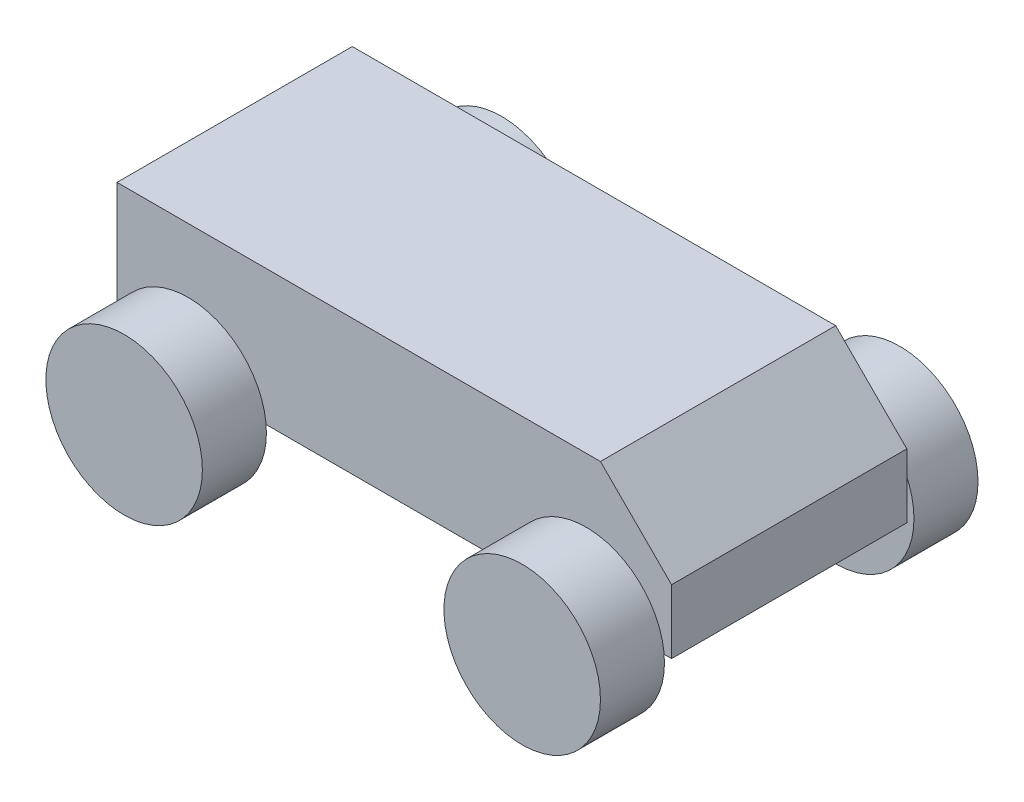
SolidWorks part; units mm, degrees
ref_plane "Front Plane" through (0, 0, 0) normal (0, 0, 1) x (1, 0, 0)
ref_plane "Top Plane" through (0, 0, 0) normal (0, 1, 0) x (1, 0, 0)
ref_plane "Right Plane" through (0, 0, 0) normal (1, 0, 0) x (0, 0, -1)
sketch "Sketch1" plane through (0, 0, 0) normal (0, 1, 0) x (1, 0, 0)
  line L1 (-495, 210) -> (495, 210)
  line L2 (-495, 210) -> (-495, -210)
  line L3 (-495, -210) -> (495, -210)
  line L4 (495, 210) -> (495, -210)
  line L5 (-495, 210) -> (495, -210) construction
  line L6 (-495, -210) -> (495, 210) construction
  point P0 (0, 0)
  dimension "D1" = 420
  dimension "D2" = 990
extrude "Boss-Extrude1" add sketch "Sketch1" along normal blind 241.3
sketch "Sketch2" plane through (0, 0, 210) normal (0, 0, 1) x (1, 0, 0)
  line L0 (-495, 0) -> (495, 0) construction
  line L1 (-355.3, 0) -> (0, 0) construction
  line L2 (0, 0) -> (355.3, 0) construction
  line L3 (-495, 241.3) -> (-495, 0) construction
  circle A0 centre (-355.3, 0) radius 139.7
  circle A1 centre (355.3, 0) radius 139.7
  dimension "D1" = 279.4
extrude "Boss-Extrude2" add sketch "Sketch2" along normal blind 114.3 from offset 12.7 separate body
mirror "Mirror2" about plane through (0, 0, 0) normal (0, 0, 1) of bodies 103 102
sketch "Sketch3" plane through (0, 0, 337) normal (0, 0, 1) x (1, 0, 0)
  circle A0 centre (-355.3, 0) radius 25.4
  circle A1 centre (355.3, 0) radius 25.4
  dimension "D1" = 50.8
extrude "Boss-Extrude3" add sketch "Sketch3" against normal up to surface (674 mm away) up to face at (495, 0, -337)
chamfer "Chamfer1" distance 127 angle 45 1 edges at (495, 241.3, 0)
sketch "Sketch4" plane through (0, 0, 210) normal (0, 0, 1) x (1, 0, 0)
  line L1 (-495, 241.3) -> (368, 241.3) construction
  line L2 (355.3, -139.7) -> (-355.3, -139.7) construction
  line L3 (-495, 241.3) -> (-495, 0) construction
  arc A0 (-660.1, 241.3) -> (-876, -139.7) centre (-1078.9553, 226.9797) cw
  circle A3 centre (-355.3, 0) radius 139.7 construction
  dimension "D1" = 381
  dimension "D3" = 419.1
  dimension "D2" = 165.1
extrude "Extrude-Thin1" [suppressed] add sketch "Sketch4" along normal up to surface and the other way up to surface separate body thin
